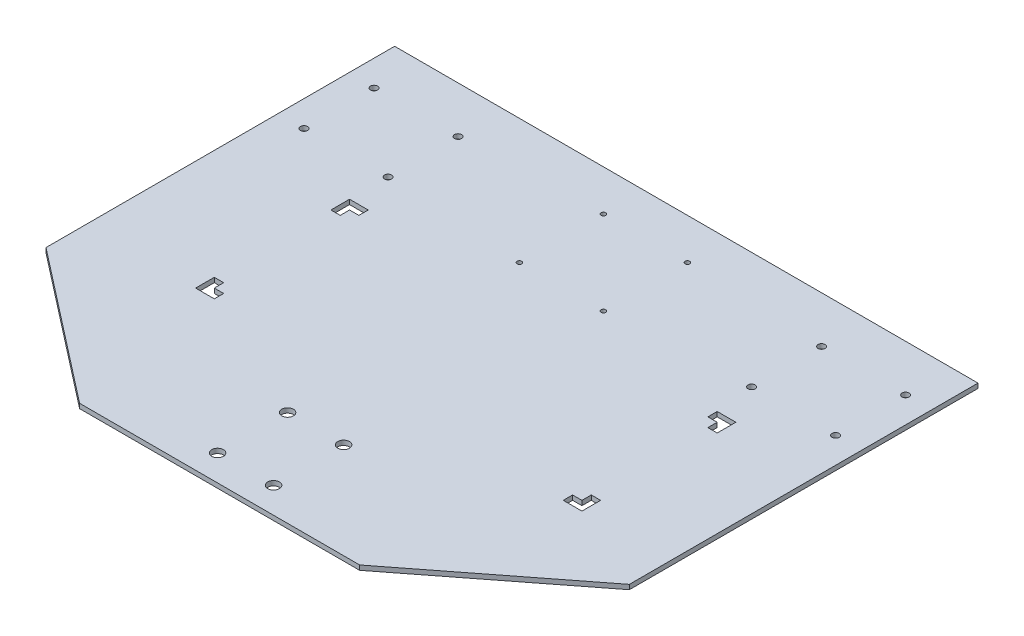
SolidWorks part; units mm, degrees
ref_plane "Front Plane" through (0, 0, 0) normal (0, 0, 1) x (1, 0, 0)
ref_plane "Top Plane" through (0, 0, 0) normal (0, 1, 0) x (1, 0, 0)
ref_plane "Right Plane" through (0, 0, 0) normal (1, 0, 0) x (0, 0, -1)
sketch "Sketch1" plane through (0, 0, 0) normal (0, 1, 0) x (1, 0, 0)
  line L5 (-125, -50) -> (-60, -100.598)
  line L11 (-60, -100.598) -> (60, -100.598)
  line L12 (-125, -50) -> (-125, 99.402)
  line L13 (-125, 99.402) -> (125, 99.402)
  line L14 (125, -50) -> (125, 99.402)
  line L15 (0, 0) -> (51.0077, 0)
  line L17 (0, 137.0957) -> (0, 99.402) construction
  line L18 (125, -50) -> (60, -100.598)
  line L26 (-71.9835, -27) -> (-2.9835, -27)
  line L27 (-71.9835, -27) -> (-71.9835, 27)
  line L32 (-71.9835, 27) -> (-2.9835, 27)
  line L33 (-2.9835, -27) -> (-2.9835, 27)
  line L35 (-69.8962, 32.9802) -> (-69.8962, 28.9802)
  line L36 (-1.0748, 27.5) -> (81.9252, 27.5)
  line L37 (-1.0748, 27.5) -> (-1.0748, -27.5)
  line L38 (-1.0748, -27.5) -> (81.9252, -27.5)
  line L39 (81.9252, 27.5) -> (81.9252, -27.5)
  line L40 (0, -100.598) -> (0, -162.6696) construction
  line L41 (85.7581, -23.0274) -> (92.5077, -27.5) construction
  line L42 (-69.8962, 28.9802) -> (-73.8962, 28.9802)
  line L43 (-73.8962, 28.9802) -> (-73.8962, 24.9802)
  line L44 (-73.8962, 24.9802) -> (-77.8962, 24.9802)
  line L45 (-77.8962, 24.9802) -> (-77.8962, 32.9802)
  line L47 (-77.8962, 32.9802) -> (-69.8962, 32.9802)
  line L48 (-77.8962, -24.9802) -> (-77.8962, -32.9802)
  line L49 (-73.8962, -24.9802) -> (-77.8962, -24.9802)
  line L50 (-73.8962, -28.9802) -> (-73.8962, -24.9802)
  line L51 (-69.8962, -28.9802) -> (-73.8962, -28.9802)
  line L52 (-69.8962, -32.9802) -> (-69.8962, -28.9802)
  line L53 (-77.8962, -32.9802) -> (-69.8962, -32.9802)
  line L60 (79.6502, 32.9802) -> (87.6502, 32.9802)
  line L61 (87.6502, 32.9802) -> (87.6502, 24.9802)
  line L62 (87.6502, 24.9802) -> (83.6502, 24.9802)
  line L63 (83.6502, 24.9802) -> (83.6502, 28.9802)
  line L64 (83.6502, 28.9802) -> (79.6502, 28.9802)
  line L65 (79.6502, 28.9802) -> (79.6502, 32.9802)
  line L66 (83.6502, -28.9802) -> (79.6502, -28.9802)
  line L67 (83.6502, -24.9802) -> (83.6502, -28.9802)
  line L68 (87.6502, -24.9802) -> (83.6502, -24.9802)
  line L69 (87.6502, -32.9802) -> (87.6502, -24.9802)
  line L70 (79.6502, -32.9802) -> (87.6502, -32.9802)
  line L71 (79.6502, -28.9802) -> (79.6502, -32.9802)
  circle A13 centre (-77.8962, 49.4674) radius 1.5
  circle A14 centre (-77.8962, 79.4674) radius 1.5
  circle A15 centre (-113.8962, 79.4674) radius 1.5
  circle A16 centre (-113.8962, 49.4674) radius 1.5
  circle A17 centre (113.8962, 49.4674) radius 1.5
  circle A18 centre (113.8962, 79.4674) radius 1.5
  circle A19 centre (77.8962, 79.4674) radius 1.5
  circle A20 centre (77.8962, 49.4674) radius 1.5
  circle A23 centre (-18, 81.8504) radius 1
  circle A24 centre (-18, 45.8504) radius 1
  circle A25 centre (18, 81.8504) radius 1
  circle A26 centre (18, 45.8504) radius 1
  circle A27 centre (-12, -59.4728) radius 2.5
  circle A28 centre (12, -59.4728) radius 2.5
  circle A29 centre (12, -89.4728) radius 2.5
  circle A30 centre (-12, -89.4728) radius 2.5
  point P0 (0, 0)
  point P1 (0, 0)
  point P2 (0, 0)
  point P8 (-125, -50)
  point P9 (-60, -100.598)
  point P34 (0, -74.4728)
  point P35 (-42.5708, -0.5098)
  point P42 (51.0077, 0)
  point P43 (0, -74.4728)
  dimension "D1" = 200
  dimension "D5" = 3
  dimension "D10" = 3
  dimension "D6" = 3
  dimension "D7" = 3
  dimension "D11" = 36
  dimension "D12" = 30
  dimension "D13" = 36
  dimension "D14" = 36
  dimension "D16" = 5
  dimension "D2" = 250
  dimension "D3" = 50
  dimension "D4" = 60
  dimension "D8" = 54
  dimension "D9" = 69
  dimension "D15" = 18
  dimension "D19" = 83
  dimension "D20" = 55
  dimension "D21" = 8
  dimension "D22" = 4
  dimension "D23" = 4
  dimension "D24" = 4
  dimension "D25" = 8
  dimension "D26" = 8
  dimension "D27" = 4
  dimension "D28" = 4
  dimension "D17" = 2
  dimension "D18" = 2
extrude "Boss-Extrude1" add sketch "Sketch1" along normal blind 2
